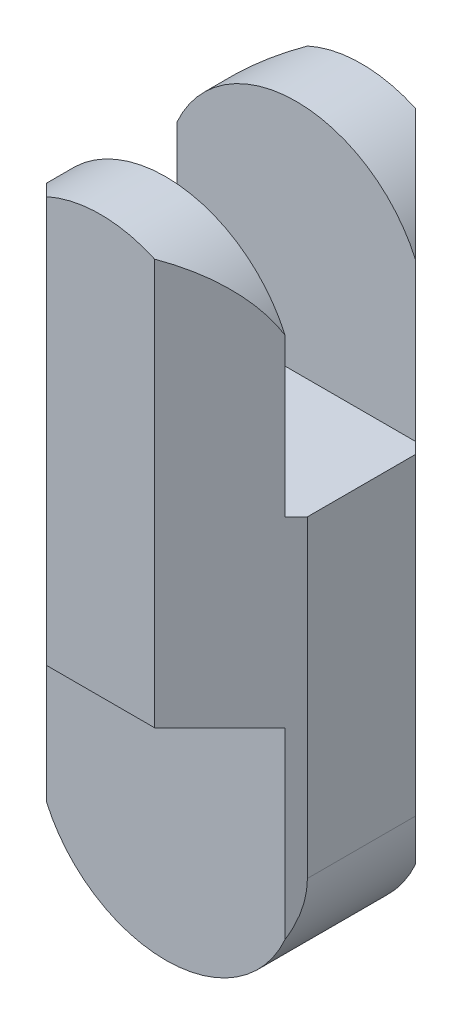
SolidWorks part; units mm, degrees
ref_plane "Front" through (0, 0, 0) normal (0, 0, 1) x (1, 0, 0)
ref_plane "Top" through (0, 0, 0) normal (0, 1, 0) x (1, 0, 0)
ref_plane "Right" through (0, 0, 0) normal (1, 0, 0) x (0, 0, -1)
sketch "草图1" plane through (0, 0, 0) normal (0, 1, 0) x (1, 0, 0)
  line L0 (-12.6518, 0) -> (13.462, 0) construction
  line L1 (0, 11.6722) -> (0, -14.1269) construction
  line L3 (10, 4.1421) -> (4.1421, 10)
  line L4 (4.1421, 10) -> (-4.1421, 10)
  line L5 (-4.1421, 10) -> (-10, 4.1421)
  line L6 (-10, 4.1421) -> (-10, -4.1421)
  line L7 (-10, -4.1421) -> (-4.1421, -10)
  line L8 (-4.1421, -10) -> (4.1421, -10)
  line L9 (4.1421, -10) -> (10, -4.1421)
  line L10 (10, -4.1421) -> (10, 4.1421)
  circle A0 centre (0, 0) radius 10 construction
extrude "凸台-拉伸1" add sketch "草图1" along normal blind 54
sketch "草图2" plane through (0, 0, 10) normal (0, 0, 1) x (1, 0, 0)
  line L0 (0, 0) -> (0, 24) construction
  line L7 (-10, 10) -> (-10, -2.3893)
  line L8 (-10, -2.3893) -> (10, -2.3893)
  line L9 (10, 10) -> (10, -2.3893)
  arc A1 (-10, 10) -> (10, 10) centre (0, 10) ccw
extrude "切除-拉伸1" cut sketch "草图2" against normal blind 66
sketch "草图4" plane through (0, 0, 10) normal (0, 0, 1) x (1, 0, 0)
  line L0 (10, 54) -> (10, 10) construction
  line L2 (-10, 10) -> (-10, 20)
  line L3 (-10, 20) -> (10, 20)
  line L4 (10, 10) -> (10, 20)
  arc A0 (-10, 10) -> (10, 10) centre (0, 10) ccw
extrude "切除-拉伸2" cut sketch "草图4" against normal blind 5
sketch "草图5" plane through (0, 0, -10) normal (0, 0, -1) x (-1, 0, 0)
  line L0 (10, 54) -> (10, 10) construction
  line L2 (-10, 10) -> (-10, 20)
  line L3 (-10, 20) -> (10, 20)
  line L4 (10, 10) -> (10, 20)
  arc A0 (-10, 10) -> (10, 10) centre (0, 10) ccw
extrude "切除-拉伸3" cut sketch "草图5" against normal blind 5
sketch "草图6" plane through (0, 0, 0) normal (0, 0, 1) x (1, 0, 0)
  line L0 (0, 54) -> (0, 0) construction
  line L1 (-4.1421, 54) -> (4.1421, 54) construction
  line L2 (10, 54) -> (10, 10) construction
  line L3 (-10, 54) -> (10, 54)
  line L4 (-10, 54) -> (-10, 34)
  line L5 (-10, 34) -> (10, 34)
  line L6 (10, 54) -> (10, 34)
  dimension "D1" = 20
extrude "切除-拉伸4" cut sketch "草图6" against normal mid plane 10
sketch "草图7" plane through (0, 0, 10) normal (0, 0, 1) x (1, 0, 0)
  line L0 (0, 54) -> (0, 0) construction
  line L1 (-4.1421, 54) -> (4.1421, 54) construction
  line L4 (-10, 42) -> (-10, 63.6612)
  line L5 (-10, 63.6612) -> (10, 63.6612)
  line L6 (10, 42) -> (10, 63.6612)
  arc A0 (10, 42) -> (-10, 42) centre (0, 42) ccw
  point P6 (0, 0)
  point P11 (0, 0)
  point P12 (0, 0)
  point P13 (0, 0)
extrude "切除-拉伸5" cut sketch "草图7" against normal blind 30
